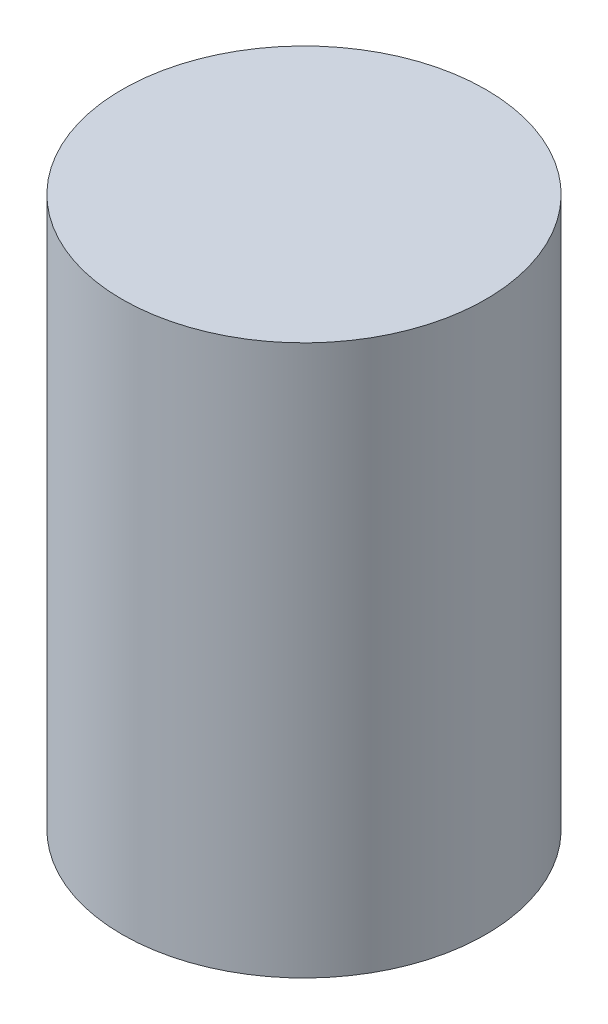
SolidWorks part; units mm, degrees
ref_plane "Front Plane" through (0, 0, 0) normal (0, 0, 1) x (1, 0, 0)
ref_plane "Top Plane" through (0, 0, 0) normal (0, 1, 0) x (1, 0, 0)
ref_plane "Right Plane" through (0, 0, 0) normal (1, 0, 0) x (0, 0, -1)
sketch "Sketch1" plane through (0, 0, 0) normal (0, 1, 0) x (1, 0, 0)
  circle A0 centre (0, 0) radius 30.226
  dimension "D1" = 60.452
extrude "Boss-Extrude1" add sketch "Sketch1" along normal blind 91.44
